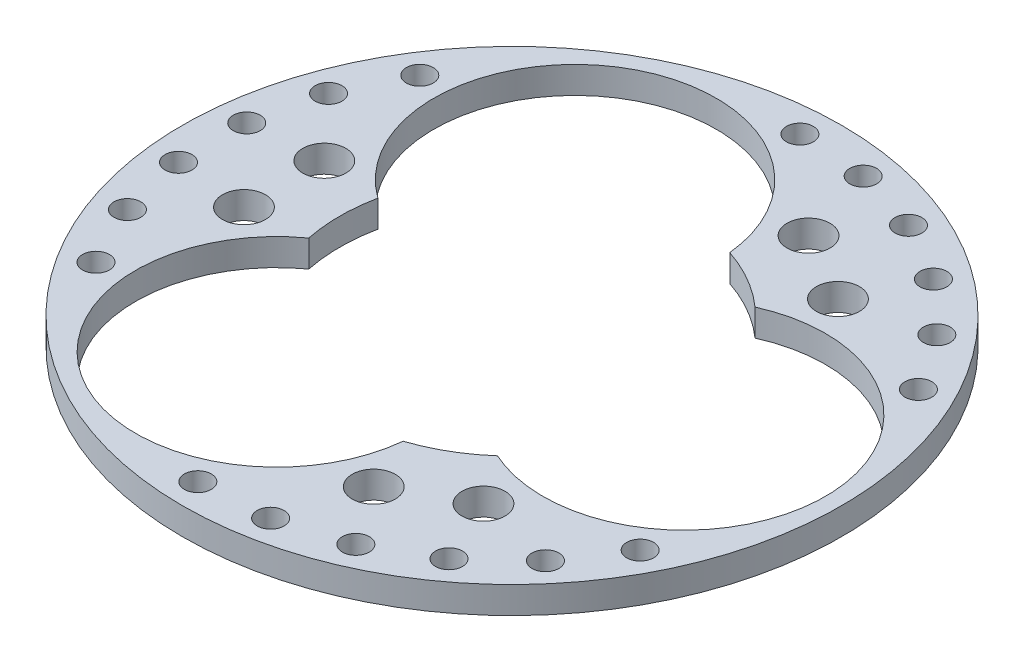
SolidWorks part; units mm, degrees
ref_plane "Front Plane" through (0, 0, 0) normal (0, 0, 1) x (1, 0, 0)
ref_plane "Top Plane" through (0, 0, 0) normal (0, 1, 0) x (1, 0, 0)
ref_plane "Right Plane" through (0, 0, 0) normal (1, 0, 0) x (0, 0, -1)
sketch "Sketch1" plane through (0, 0, 0) normal (0, 1, 0) x (1, 0, 0)
  circle A0 centre (-105.4459, 36.8665) radius 5
  circle A1 centre (-111.1501, 12.1589) radius 5
  circle A2 centre (-84.5635, 14.4138) radius 8
  circle A3 centre (0.13, -0.5199) radius 122.5
  circle A4 centre (-84.5635, -15.4536) radius 8
  circle A5 centre (-105.4459, -37.9063) radius 5
  circle A6 centre (-111.1501, -13.1987) radius 5
  arc A7 (20.3626, 60.1978) -> (-62.5694, 12.317) centre (-31.87, 54.9057) ccw
  circle A8 centre (-94.3299, 59.6577) radius 5
  circle A9 centre (-4.7554, 111.3735) radius 5
  circle A10 centre (20.5404, 109.6046) radius 5
  circle A11 centre (-4.7554, -112.4133) radius 5
  circle A12 centre (20.5404, -110.6445) radius 5
  circle A13 centre (44.7899, -103.2306) radius 5
  circle A14 centre (66.7501, -90.5519) radius 5
  circle A15 centre (85.2954, -73.2581) radius 5
  circle A16 centre (99.4752, -52.2357) radius 5
  circle A17 centre (55.4097, -66.3997) radius 8
  circle A18 centre (29.5437, -81.3335) radius 8
  circle A19 centre (-94.3299, -60.6975) radius 5
  arc A20 (-62.5694, 12.317) -> (-62.5694, -13.3568) centre (0.13, -0.5199) ccw
  arc A21 (-62.5694, -13.3568) -> (20.3626, -61.2376) centre (-31.87, -55.9455) ccw
  arc A22 (20.3626, -61.2376) -> (42.5968, -48.4007) centre (0.13, -0.5199) ccw
  arc A23 (42.5968, -48.4007) -> (42.5968, 47.3609) centre (64.13, -0.5199) ccw
  arc A24 (42.5968, 47.3609) -> (20.3626, 60.1978) centre (0.13, -0.5199) ccw
  circle A25 centre (29.5437, 80.2937) radius 8
  circle A26 centre (55.4097, 65.3599) radius 8
  circle A27 centre (99.4752, 51.1959) radius 5
  circle A28 centre (85.2954, 72.2183) radius 5
  circle A29 centre (66.7501, 89.5121) radius 5
  circle A30 centre (44.7899, 102.1908) radius 5
extrude "Boss-Extrude1" add sketch "Sketch1" along normal blind 10
